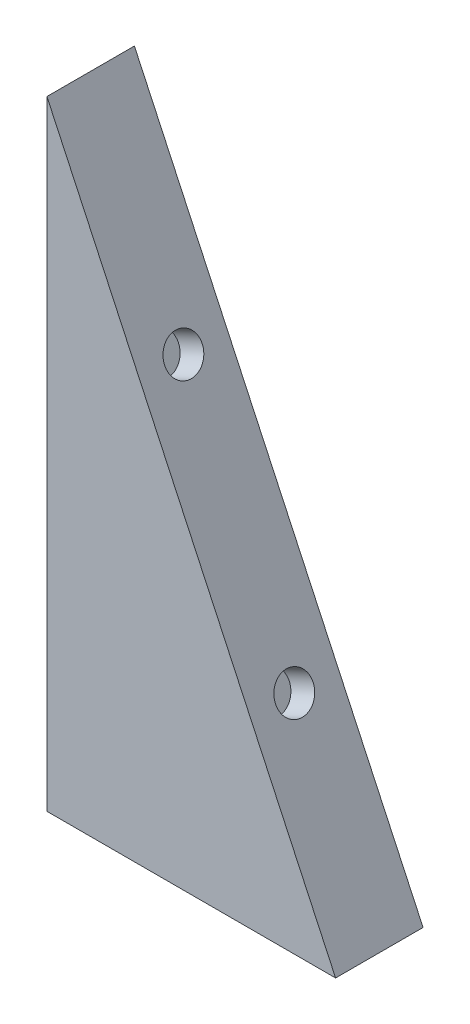
SolidWorks part; units mm, degrees
ref_plane "Front" through (0, 0, 0) normal (0, 0, 1) x (1, 0, 0)
ref_plane "Top" through (0, 0, 0) normal (0, 1, 0) x (1, 0, 0)
ref_plane "Right" through (0, 0, 0) normal (1, 0, 0) x (0, 0, -1)
sketch "Sketch1" plane through (0, 0, 0) normal (0, 0, 1) x (1, 0, 0)
  line L0 (0, 70.7687) -> (0, 0)
  line L1 (0, 0) -> (33, 0)
  line L2 (33, 0) -> (0, 70.7687)
  dimension "D1" = 33
  dimension "D2" = 65
extrude "Boss-Extrude1" add sketch "Sketch1" along normal blind 10
sketch "Sketch2" plane through (0, 0, 0) normal (0, -1, 0) x (-1, 0, 0)
  line L0 (-16.5, -10) -> (-16.5, 0) construction
  line L1 (-13.6, -6.9) -> (-19.4, -6.9)
  line L2 (-13.6, -6.9) -> (-13.6, -3.1)
  line L3 (-13.6, -3.1) -> (-19.4, -3.1)
  line L4 (-19.4, -6.9) -> (-19.4, -3.1)
  line L5 (-13.6, -6.9) -> (-19.4, -3.1) construction
  line L6 (-13.6, -3.1) -> (-19.4, -6.9) construction
  line L7 (0, -10) -> (-33, -10) construction
  line L8 (0, 0) -> (-33, 0) construction
  line L9 (0, -5) -> (-33, -5) construction
  line L10 (0, -10) -> (0, 0) construction
  line L11 (-33, -10) -> (-33, 0) construction
  point P0 (-16.5, -5)
  point P18 (-16.5, -5)
  dimension "D1" = 5.8
  dimension "D2" = 3.8
extrude "Boss-Extrude2" add sketch "Sketch2" along normal blind 2
sketch "Sketch3" plane through (0, 0, 0) normal (0, -1, 0) x (-1, 0, 0)
  circle A0 centre (-23.3315, -4) radius 2.15
  circle A1 centre (-8.5515, -4) radius 2.15
  dimension "D1" = 4.3
extrude "Cut-Extrude1" cut sketch "Sketch3" against normal blind 12
sketch "Sketch4" plane through (0, 0, 0) normal (0, 0, -1) x (-1, 0, 0)
  line L0 (-27.1315, 3.25) -> (-27.1315, 5) construction
  line L1 (-25.4815, -1.25) -> (-21.1815, -1.25) construction
  line L2 (-19.5315, 3.25) -> (-19.5315, 5) construction
  line L3 (-25.4815, 0) -> (-21.1815, 0)
  line L4 (-21.1815, 0) -> (-10.7015, 0) construction
  line L5 (-15.9415, 0) -> (-15.9415, 7.9966) construction
  line L7 (-12.3515, 3.25) -> (-12.3515, 5) construction
  line L8 (-25.4815, 0) -> (-25.4815, -2.5) construction
  line L10 (-19.5315, 5) -> (-19.5315, 3.25)
  line L12 (-27.1315, 3.25) -> (-27.1315, 5)
  line L13 (-23.3315, 5) -> (-23.3315, -5) construction
  line L14 (-35.3315, -5) -> (66.6685, -5) construction
  line L15 (-21.1815, -2.5) -> (-21.1815, 0) construction
  line L20 (-27.1315, 3.25) -> (-19.5315, 3.25)
  line L21 (-19.5315, 3.25) -> (-19.5315, 6.75)
  line L22 (-19.5315, 6.75) -> (-27.1315, 6.75)
  line L23 (-27.1315, 6.75) -> (-27.1315, 3.25)
  line L24 (-27.1315, 5) -> (-19.5315, 5) construction
  line L25 (-4.7515, 3.25) -> (-4.7515, 5) construction
  line L26 (-4.7515, 6.75) -> (-4.7515, 3.25)
  line L27 (-12.3515, 6.75) -> (-4.7515, 6.75)
  line L28 (-12.3515, 3.25) -> (-12.3515, 6.75)
  line L29 (-4.7515, 3.25) -> (-12.3515, 3.25)
  line L30 (-4.7515, 3.25) -> (-4.7515, 5)
  line L31 (-12.3515, 5) -> (-12.3515, 3.25)
  point P5 (-23.3315, 0)
  dimension "D1" = 7.6
  dimension "D2" = 3.8
  dimension "D3" = 3.5
extrude "Cut-Extrude2" cut sketch "Sketch4" against normal blind 6.5
sketch "Sketch5" plane through (0, 0, 0) normal (0, 0, -1) x (-1, 0, 0)
  line L0 (-21.1815, 0) -> (-10.7015, 0) construction
  line L1 (0, 0) -> (-33, 0) construction
  line L2 (-10.7015, 0) -> (-10.7015, -2.5) construction
  line L3 (-15.9415, 0) -> (-15.9415, 10.1006) construction
  line L4 (-27.1315, 6.75) -> (-27.1315, 3.25)
  line L5 (-27.1315, 3.25) -> (-19.5315, 3.25)
  line L6 (-19.5315, 3.25) -> (-19.5315, 6.75)
  line L7 (-19.5315, 6.75) -> (-27.1315, 6.75)
  line L8 (-12.3515, 6.75) -> (-4.7515, 6.75)
  line L9 (-12.3515, 3.25) -> (-12.3515, 6.75)
  line L10 (-4.7515, 3.25) -> (-12.3515, 3.25)
  line L11 (-4.7515, 6.75) -> (-4.7515, 3.25)
extrude "Cut-Extrude3" cut sketch "Sketch5" against normal blind 6.5
sketch "Sketch6" plane through (27.106, 12.6397, 0) normal (0.9063, 0.4226, 0) x (0, 0, -1)
  line L0 (0, -13.9464) -> (0, 64.1382) construction
  line L1 (-10, -13.9464) -> (0, -13.9464) construction
  circle A0 centre (-5, 9.0536) radius 2.15
  circle A1 centre (-5, 39.0536) radius 2.15
  dimension "D3" = 4.3
  dimension "D4" = 23
  dimension "D1" = 5
  dimension "D2" = 5
  dimension "D5" = 53
extrude "Cut-Extrude4" cut sketch "Sketch6" against normal blind 7.3
sketch "Sketch7" plane through (0, 0, 10) normal (0, 0, 1) x (1, 0, 0)
  line L0 (6.2476, 50.1994) -> (3.3587, 48.823)
  line L1 (3.3587, 48.823) -> (6.6275, 41.9619)
  line L2 (6.6275, 41.9619) -> (9.5164, 43.3383)
  line L3 (9.5164, 43.3383) -> (6.2476, 50.1994)
  line L4 (18.9825, 23.0383) -> (22.1372, 16.1239)
  line L5 (22.1372, 16.1239) -> (19.2259, 14.7956)
  line L6 (19.2259, 14.7956) -> (16.0712, 21.7099)
  line L7 (16.0712, 21.7099) -> (18.9825, 23.0383)
extrude "Cut-Extrude5" cut sketch "Sketch7" along normal blind 7.5 from surface at -10 starting at face at (8.5515, 5, 0)
sketch "Sketch8" plane through (0, 0, 0) normal (0, 0, -1) x (-1, 0, 0)
  line L0 (-27.1315, 6.75) -> (-19.5315, 6.75)
  line L1 (-19.5315, 6.75) -> (-19.5315, 3.25)
  line L2 (-19.5315, 3.25) -> (-27.1315, 3.25)
  line L3 (-27.1315, 3.25) -> (-27.1315, 6.75)
  line L4 (-12.3515, 6.75) -> (-12.3515, 3.25)
  line L5 (-12.3515, 3.25) -> (-4.7515, 3.25)
  line L6 (-4.7515, 3.25) -> (-4.7515, 6.75)
  line L7 (-4.7515, 6.75) -> (-12.3515, 6.75)
  line L8 (-22.1372, 16.1239) -> (-19.2259, 14.7956)
  line L9 (-19.2259, 14.7956) -> (-16.0712, 21.7099)
  line L10 (-16.0712, 21.7099) -> (-18.9825, 23.0383)
  line L11 (-18.9825, 23.0383) -> (-22.1372, 16.1239)
  line L12 (-9.5164, 43.3383) -> (-6.6275, 41.9619)
  line L13 (-6.6275, 41.9619) -> (-3.3587, 48.823)
  line L14 (-3.3587, 48.823) -> (-6.2476, 50.1994)
  line L15 (-6.2476, 50.1994) -> (-9.5164, 43.3383)
extrude "Cut-Extrude6" cut sketch "Sketch8" against normal blind 8.75
